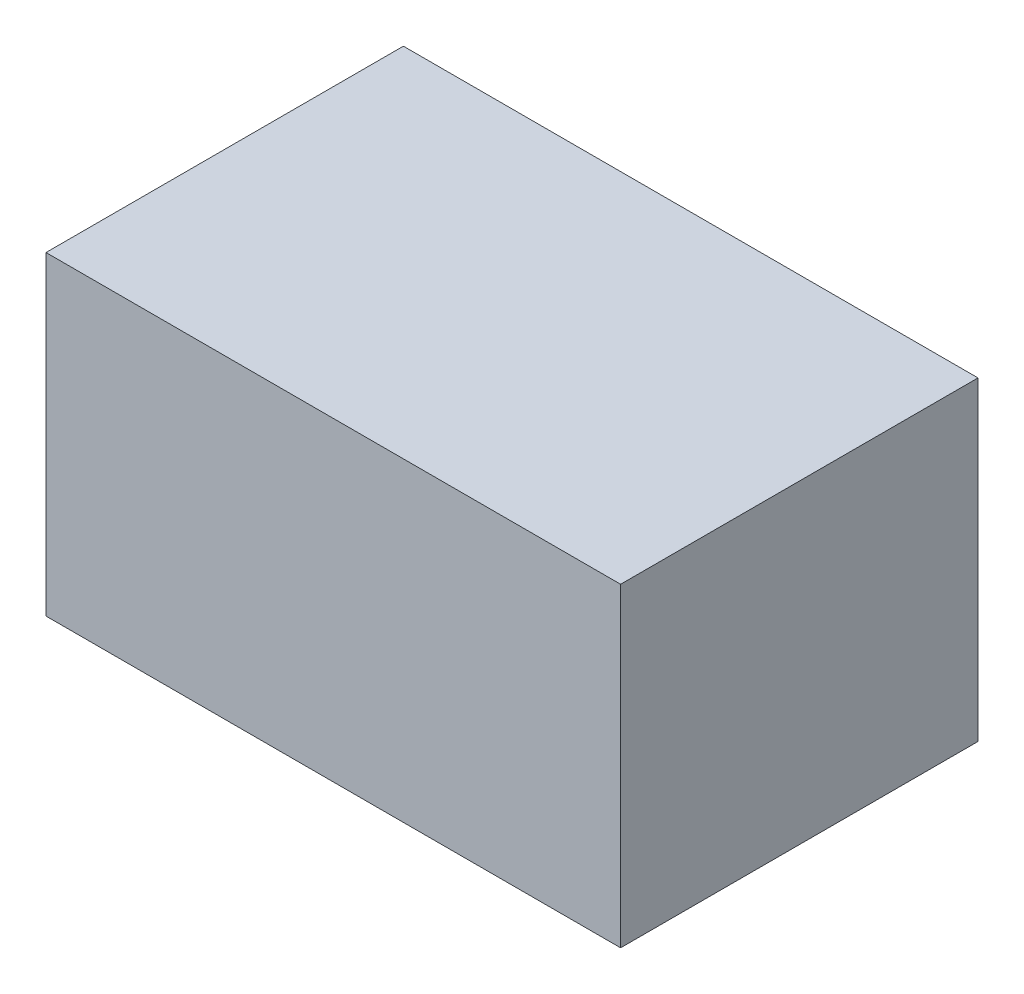
SolidWorks part; units mm, degrees
ref_plane "Front Plane" through (0, 0, 0) normal (0, 0, 1) x (1, 0, 0)
ref_plane "Top Plane" through (0, 0, 0) normal (0, 1, 0) x (1, 0, 0)
ref_plane "Right Plane" through (0, 0, 0) normal (1, 0, 0) x (0, 0, -1)
sketch "CurveSketch" plane through (0, 0, 0) normal (0, 0, 1) x (1, 0, 0)
  line L0 (-20.0525, -1.8635) -> (11.6665, -1.8635)
  line L1 (11.6665, -1.8635) -> (11.6665, 15.5175)
  line L2 (11.6665, 15.5175) -> (-20.0525, 15.5175)
  line L3 (-20.0525, 15.5175) -> (-20.0525, -1.8635)
extrude "CurveBoss" add sketch "CurveSketch" along normal blind 19.729
